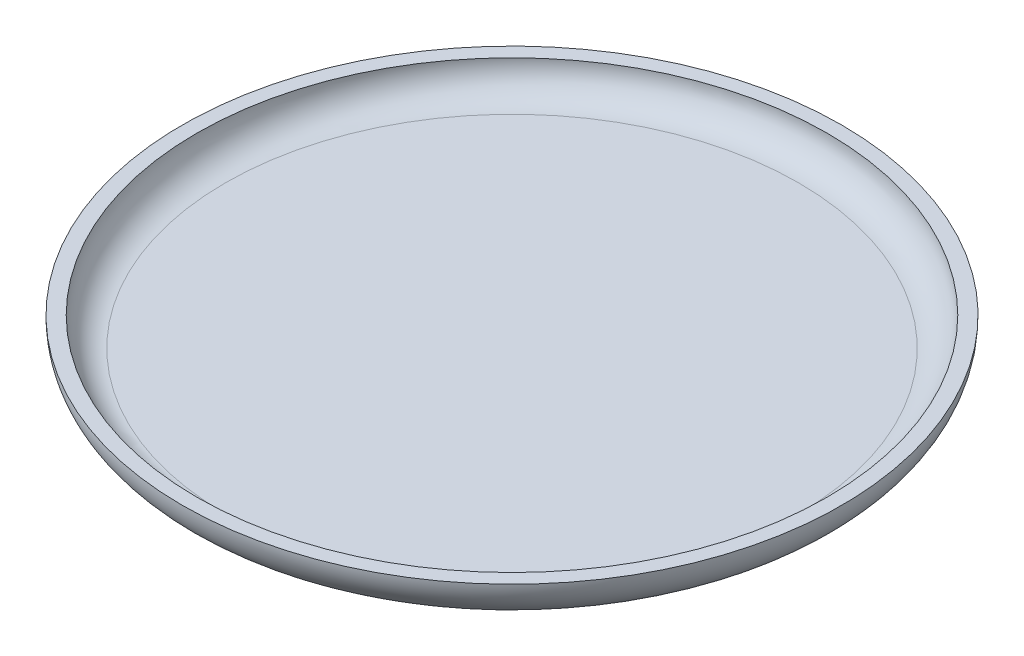
SolidWorks part; units mm, degrees
material "Maple"
ref_plane "Front Plane" through (0, 0, 0) normal (0, 0, 1) x (1, 0, 0)
ref_plane "Top Plane" through (0, 0, 0) normal (0, 1, 0) x (1, 0, 0)
ref_plane "Right Plane" through (0, 0, 0) normal (1, 0, 0) x (0, 0, -1)
sketch "Sketch1" plane through (0, 0, 0) normal (0, 0, 1) x (1, 0, 0)
  line L0 (139.7, 19.05) -> (146.05, 19.05)
  line L1 (0, 0) -> (127, 0)
  line L2 (0, 0) -> (0, 6.35)
  line L3 (0, 6.35) -> (127, 6.35)
  line L4 (127, 0) -> (127, 6.35)
  line L5 (146.05, 19.05) -> (146.05, -56.8901) construction
  arc A0 (127, 6.35) -> (139.7, 19.05) centre (127, 19.05) ccw
  arc A1 (127, 0) -> (146.05, 19.05) centre (127, 19.05) ccw
  dimension "D1" = 6.35
  dimension "D2" = 6.35
  dimension "D3" = 127
  dimension "D4" = 12.7
revolve "Revolve1" add sketch "Sketch1" angle 360 about L2
sketch "Sketch2" plane through (0, 0, 0) normal (0, -1, 0) x (1, 0, 0)
  circle A0 centre (0, 0) radius 6.35
  dimension "D1" = 12.7
extrude "Cut-Extrude1" cut sketch "Sketch2" against normal blind 4.826
